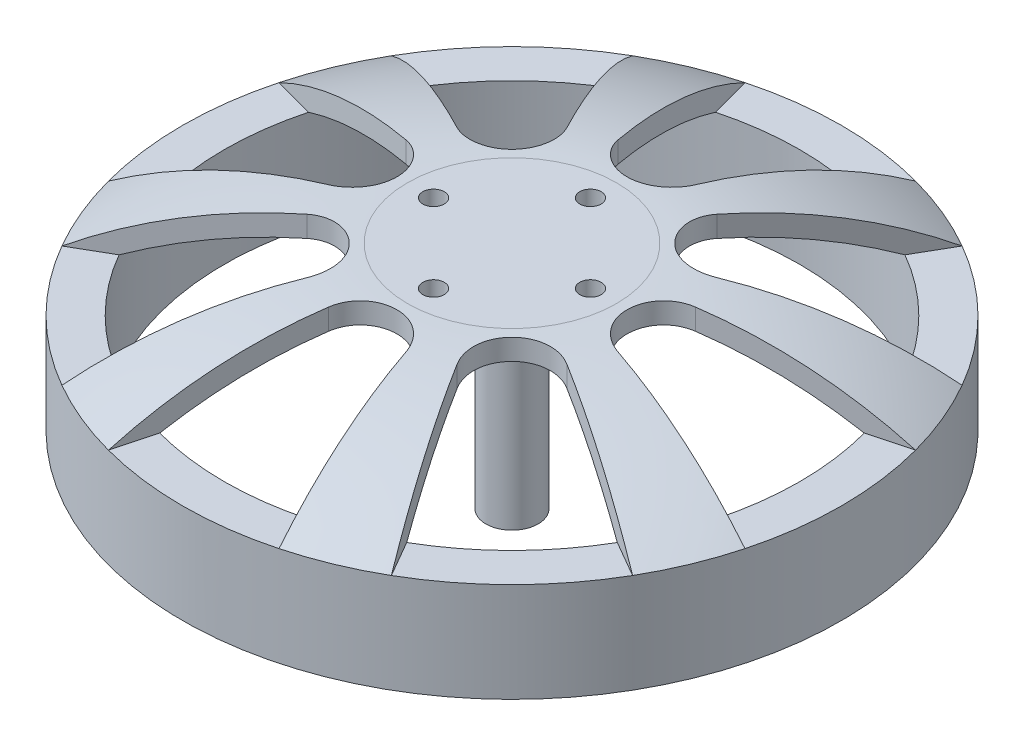
SolidWorks part; units mm, degrees
ref_plane "Front Plane" through (0, 0, 0) normal (0, 0, 1) x (1, 0, 0)
ref_plane "Top Plane" through (0, 0, 0) normal (0, 1, 0) x (1, 0, 0)
ref_plane "Right Plane" through (0, 0, 0) normal (1, 0, 0) x (0, 0, -1)
sketch "Sketch2" plane through (0, 0, 0) normal (0, 0, 1) x (1, 0, 0)
  line L0 (0, 0) -> (0, 22)
  line L1 (0, 11) -> (-31.5, 11) construction
  line L2 (-31.5, 16) -> (-31.5, 6.5)
  line L3 (0, 22) -> (-10, 22)
  line L4 (-31.5, 6.5) -> (-27.5, 6.5)
  line L5 (-27.5, 6.5) -> (-27.5, 16)
  line L6 (0, 0) -> (-2.5, 0)
  line L7 (-2.5, 0) -> (-2.5, 20)
  line L8 (-2.5, 20) -> (-10, 20)
  arc A0 (-10, 22) -> (-31.5, 16) centre (-10, -19.5208) ccw
  arc A1 (-10, 20) -> (-27.5, 16) centre (-10, -20.2812) ccw
  dimension "D1" = 22
  dimension "D2" = 31.5
  dimension "D3" = 10
  dimension "D4" = 9.5
  dimension "D5" = 10
  dimension "D6" = 4
  dimension "D7" = 2.5
  dimension "D8" = 2
revolve "Revolve1" add sketch "Sketch2" angle 360 about L0
sketch "Sketch3" plane through (0, 22, 0) normal (0, 1, 0) x (1, 0, 0)
  line L0 (0, 0) -> (0, 31.5) construction
  line L1 (-8.1528, 30.4267) -> (-3.7103, 13.847)
  line L2 (3.7103, 13.847) -> (8.1528, 30.4267)
  circle A0 centre (0, 0) radius 31.5 construction
  arc A1 (-8.1528, 30.4267) -> (8.1528, 30.4267) centre (0, 0) cw
  arc A2 (-3.7103, 13.847) -> (3.7103, 13.847) centre (0, 14.8412) ccw
  point P10 (0, 11)
  dimension "D1" = 11
  dimension "D2" = 30
extrude "Cut-Extrude1" cut sketch "Sketch3" against normal blind 6
pattern_circular "CirPattern1" count 8 over 360 about axis through (0, 0, 0) along (0, 1, 0) of "Cut-Extrude1"
hole_wizard "M2.5x0.45 Tapped Hole1" positions "Sketch5" profile "Sketch4" tap size "M2.5x0.45" standard "ANSI Metric" end condition up to next
sketch "Sketch5" plane through (0, 22, 0) normal (0, 1, 0) x (1, 0, 0)
  line L0 (0, 7.5) -> (0, -7.5) construction
  line L3 (7.5, 0) -> (-7.5, 0) construction
  point P0 (0, 7.5)
  point P2 (7.5, 0)
  point P4 (0, -7.5)
  point P6 (-7.5, 0)
  dimension "D1" = 15
sketch "Sketch4" plane through (0, 22, -7.5) normal (1, 0, 0) x (0, 0, 1)
  line L0 (0, 0) -> (0, 2)
  line L1 (0, 2) -> (1.025, 2)
  line L2 (1.025, 2) -> (1.025, 0)
  line L5 (1.025, 0) -> (0, 0)
  line L11 (0, -6.35) -> (0, 107.95) construction
  dimension "Thread Major Dia." = 2.05
  dimension "Thru Tap Drill Depth" = 2
